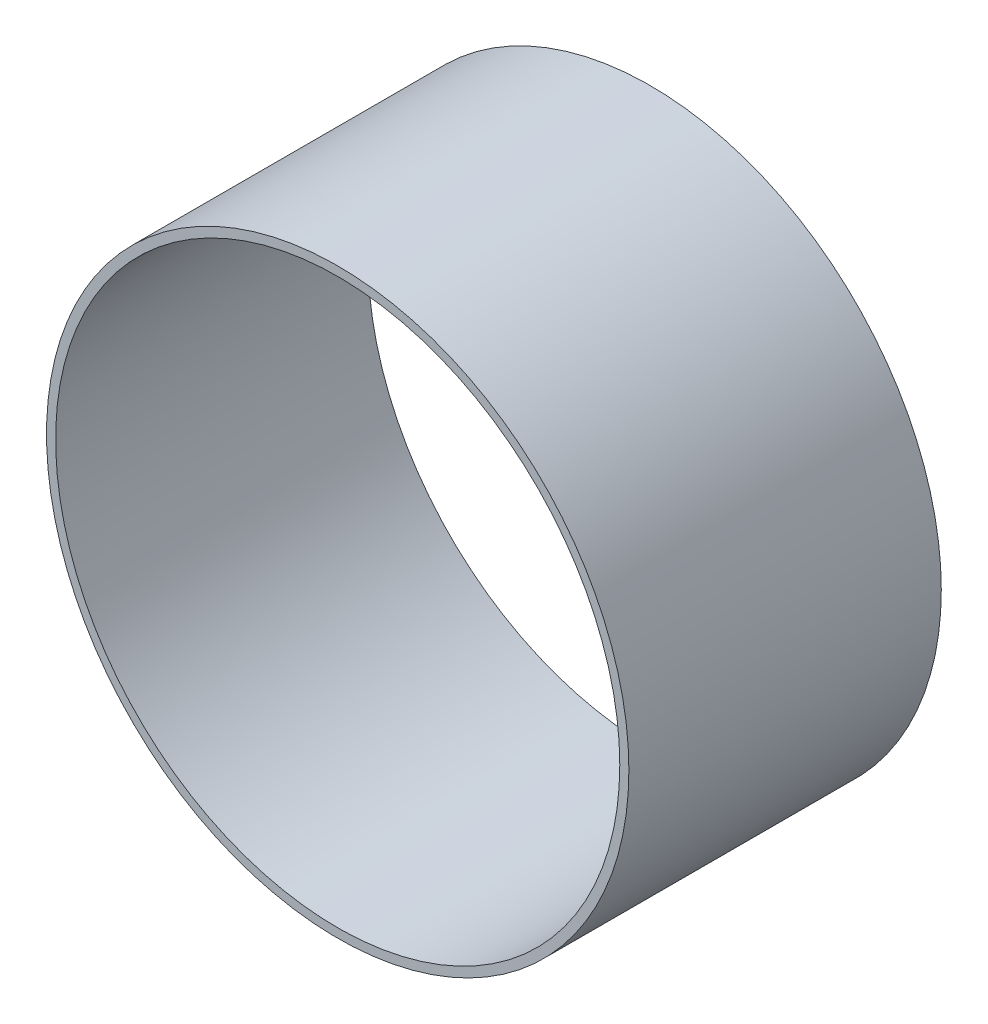
SolidWorks part; units mm, degrees
ref_plane "Спереди" through (0, 0, 0) normal (0, 0, 1) x (1, 0, 0)
ref_plane "Сверху" through (0, 0, 0) normal (0, 1, 0) x (1, 0, 0)
ref_plane "Справа" through (0, 0, 0) normal (1, 0, 0) x (0, 0, -1)
sketch "Эскиз1" plane through (0, 0, 0) normal (0, 0, 1) x (1, 0, 0)
  circle A0 centre (0, 0) radius 96
  circle A1 centre (0, 0) radius 93
extrude "Rim_reference" add sketch "Эскиз1" along normal blind 103 from offset 44.5
